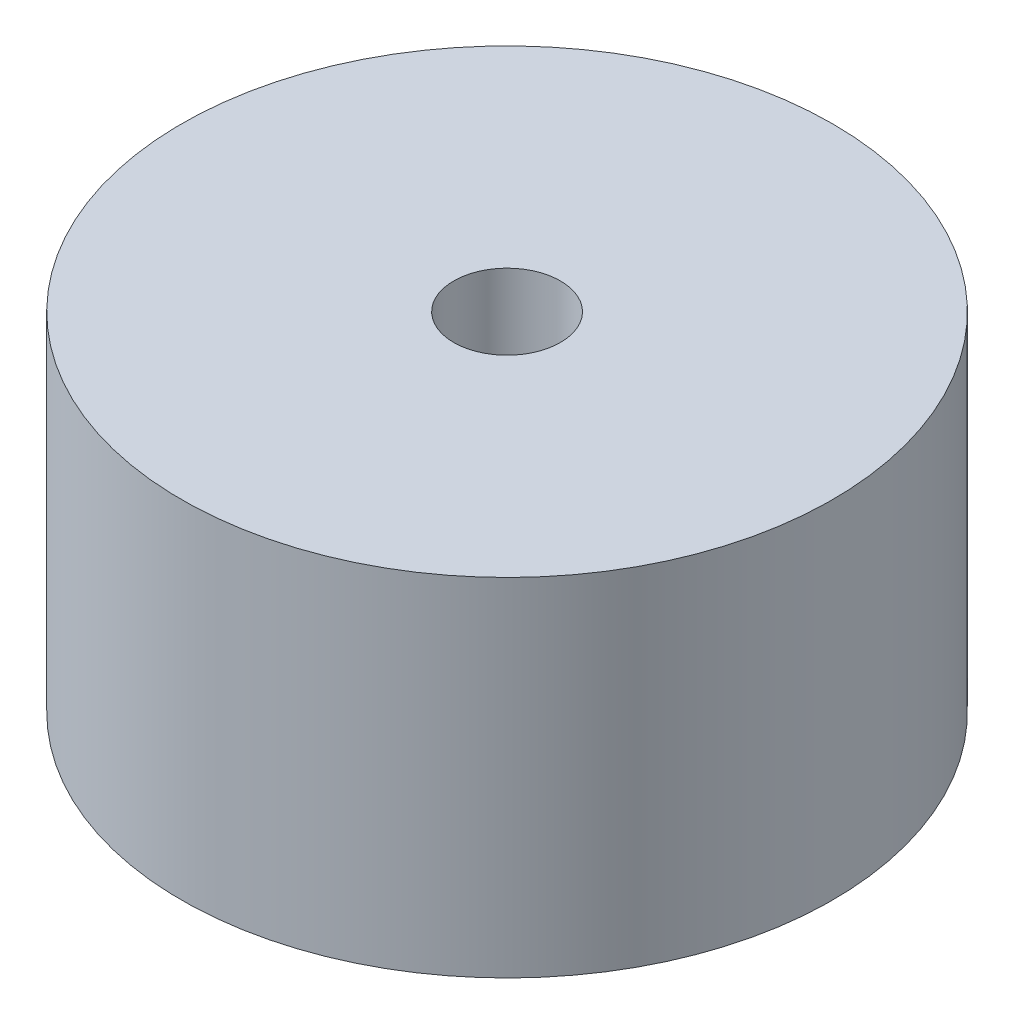
SolidWorks part; units mm, degrees
ref_plane "Plan de face" through (0, 0, 0) normal (0, 0, 1) x (1, 0, 0)
ref_plane "Plan de dessus" through (0, 0, 0) normal (0, 1, 0) x (1, 0, 0)
ref_plane "Plan de droite" through (0, 0, 0) normal (1, 0, 0) x (0, 0, -1)
sketch "Esquisse1" plane through (0, 0, 0) normal (0, 1, 0) x (1, 0, 0)
  circle A0 centre (19.4432, -18.3069) radius 6.1
extrude "Boss.-Extru.1" add sketch "Esquisse1" along normal blind 6.5
sketch "Esquisse2" plane through (0, 6.5, 0) normal (0, 1, 0) x (1, 0, 0)
  circle A0 centre (19.4432, -18.3069) radius 1
  circle A1 centre (19.4432, -18.3069) radius 6.1 construction
  point P4 (0, 0)
  point P6 (19.3692, -16.6089)
  dimension "D1" = 0
  dimension "D2" = 0
extrude "Enlèv. mat.-Extru.1" cut sketch "Esquisse2" against normal blind 3
